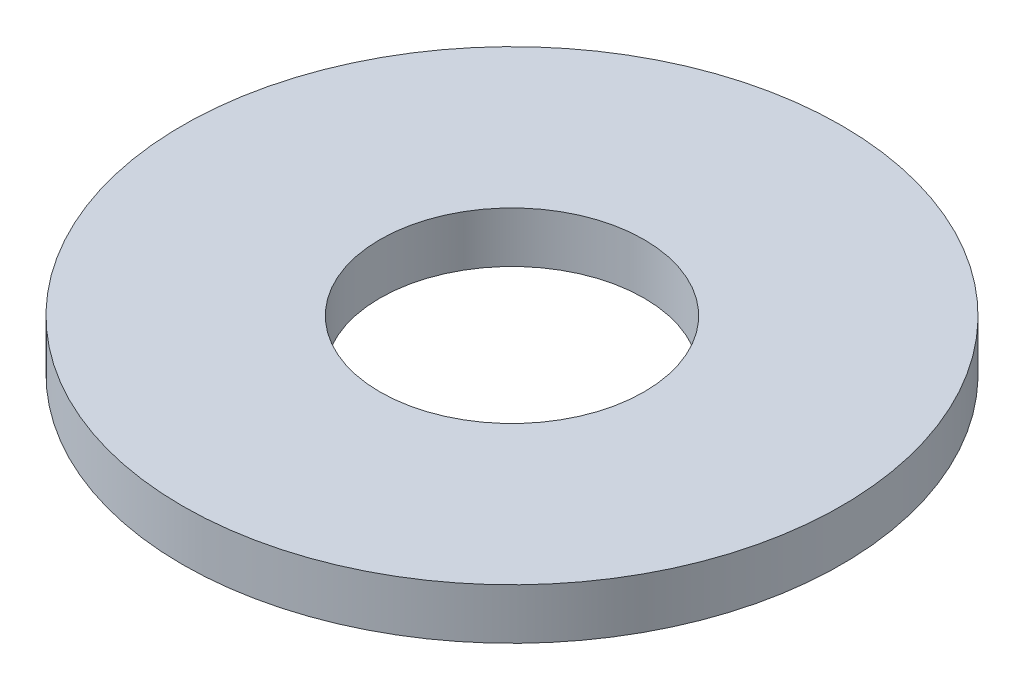
SolidWorks part; units mm, degrees
ref_plane "Front Plane" through (0, 0, 0) normal (0, 0, 1) x (1, 0, 0)
ref_plane "Top Plane" through (0, 0, 0) normal (0, 1, 0) x (1, 0, 0)
ref_plane "Right Plane" through (0, 0, 0) normal (1, 0, 0) x (0, 0, -1)
sketch "Sketch1" plane through (0, 0, 0) normal (0, 1, 0) x (1, 0, 0)
  circle A0 centre (0, 0) radius 3.9624
  dimension "OD" = 7.9248
extrude "Boss-Extrude1" add sketch "Sketch1" along normal blind 0.6096
sketch "Sketch5" plane through (0, 0.6096, 0) normal (0, 1, 0) x (-1, 0, 0)
  circle A0 centre (0, 0) radius 1.5875
  dimension "ID" = 3.175
extrude "Cut-Extrude1" cut sketch "Sketch5" against normal through all
